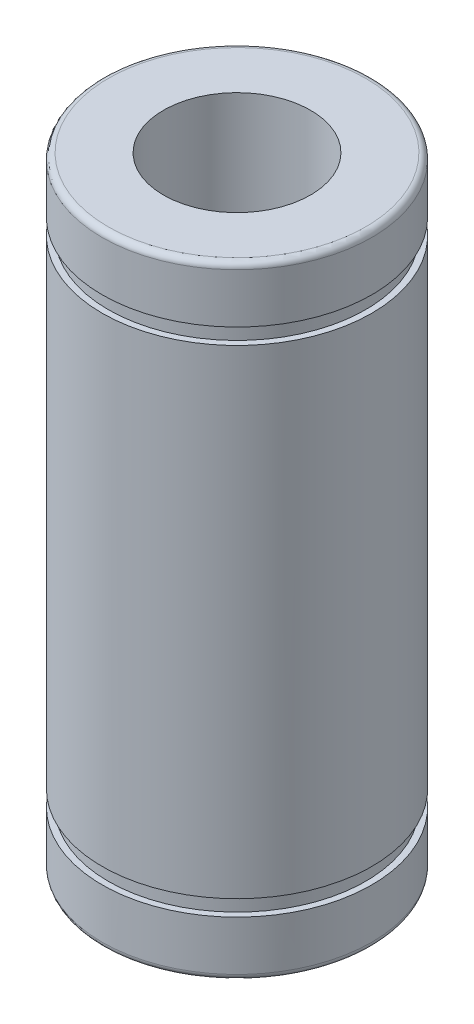
SolidWorks part; units mm, degrees
ref_plane "Frontal" through (0, 0, 0) normal (0, 0, 1) x (1, 0, 0)
ref_plane "Superior" through (0, 0, 0) normal (0, 1, 0) x (1, 0, 0)
ref_plane "Direito" through (0, 0, 0) normal (1, 0, 0) x (0, 0, -1)
sketch "Esboço1" plane through (0, 0, 0) normal (0, 1, 0) x (1, 0, 0)
  circle A0 centre (0, 0) radius 11
  circle A1 centre (0, 0) radius 6
  dimension "D1" = 12
  dimension "D2" = 22
extrude "Ressalto-extrusão1" add sketch "Esboço1" along normal blind 50.8
sketch "Esboço2" plane through (0, 50.8, 0) normal (0, 1, 0) x (1, 0, 0)
  circle A0 centre (0, 0) radius 11
  circle A1 centre (0, 0) radius 10.5
  dimension "D1" = 21
  dimension "D2" = 22
extrude "Corte-extrusão1" cut sketch "Esboço2" against normal blind 1.3 from offset 4.55 offset against normal yes
sketch "Esboço3" plane through (0, 0, 0) normal (0, -1, 0) x (1, 0, 0)
  circle A0 centre (0, 0) radius 11
  circle A1 centre (0, 0) radius 10.5
  dimension "D1" = 21
  dimension "D2" = 22
extrude "Corte-extrusão2" cut sketch "Esboço3" against normal blind 1.3 from offset 4.55 offset against normal yes
fillet "Filete1" radius 0.5 2 edges at (0, 50.8, 11) (0, 0, 11)
